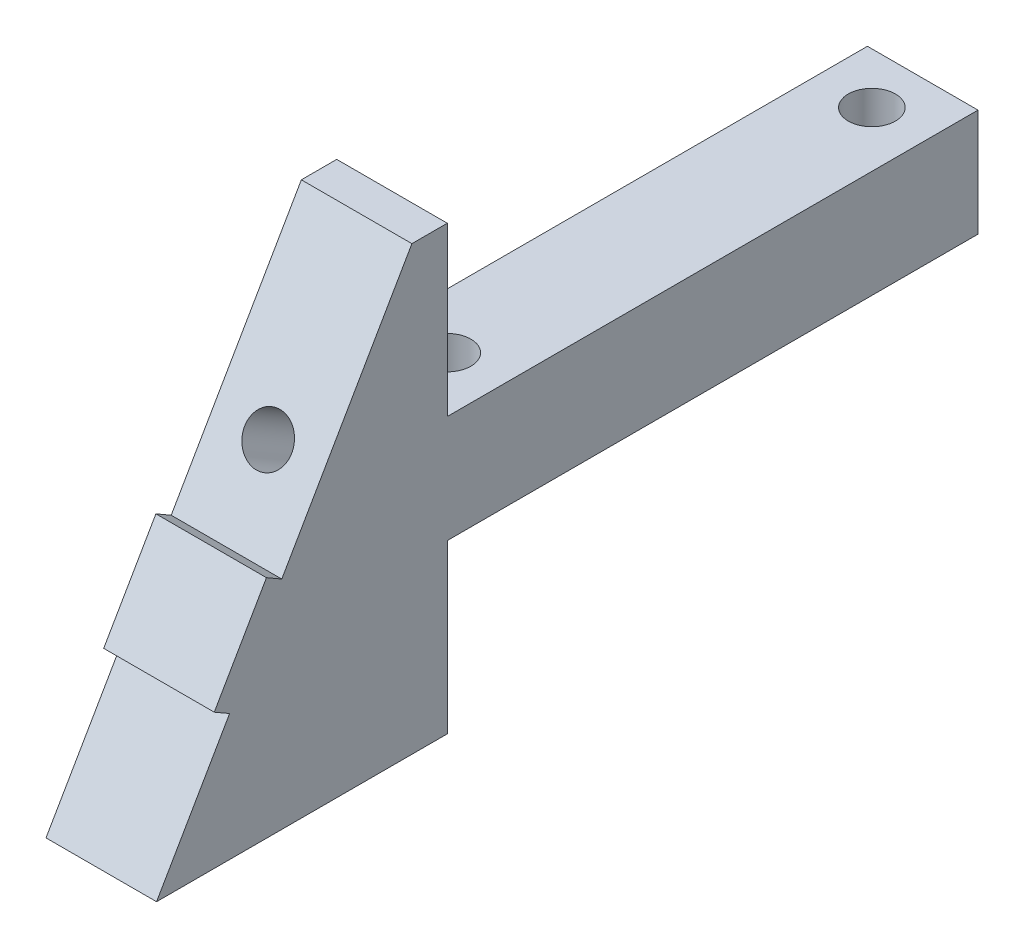
SolidWorks part; units mm, degrees
material "6061-T6 (SS)"
ref_plane "Front Plane" through (0, 0, 0) normal (0, 0, 1) x (1, 0, 0)
ref_plane "Top Plane" through (0, 0, 0) normal (0, 1, 0) x (1, 0, 0)
ref_plane "Right Plane" through (0, 0, 0) normal (1, 0, 0) x (0, 0, -1)
sketch "Sketch1" plane through (0, 0, 0) normal (1, 0, 0) x (0, 0, -1)
  line L0 (0, 0) -> (0, 25.4)
  line L1 (0, 25.4) -> (-2.032, 25.4)
  line L2 (-16.6967, 0) -> (0, 0)
  line L3 (-2.032, 25.4) -> (-16.6967, 0)
  dimension "D1" = 2.032
  dimension "D2" = 25.4
  dimension "D3" = 30
extrude "Boss-Extrude1" add sketch "Sketch1" along normal blind 6.35
sketch "Sketch2" plane through (0, 0, 0) normal (0, 0, -1) x (-1, 0, 0)
  line L0 (-6.35, 0) -> (-6.35, 25.4) construction
  line L1 (-6.35, 15.875) -> (0, 15.875)
  line L2 (-6.35, 15.875) -> (-6.35, 9.525)
  line L3 (-6.35, 9.525) -> (0, 9.525)
  line L4 (0, 15.875) -> (0, 9.525)
  line L5 (0, 0) -> (0, 25.4) construction
  line L7 (-6.35, 25.4) -> (0, 25.4) construction
  dimension "D1" = 6.35
  dimension "D2" = 9.525
extrude "Boss-Extrude2" add sketch "Sketch2" along normal blind 30.48
sketch "Sketch10" plane through (0, 7.2299, 12.5225) normal (0, 0.5, 0.866) x (1, 0, 0)
  line L0 (0, 20.981) -> (0, -8.3483) construction
  line L1 (0, 6.122) -> (6.35, 6.122)
  line L2 (0, 6.122) -> (0, -0.0502)
  line L3 (0, -0.0502) -> (6.35, -0.0502)
  line L4 (6.35, 6.122) -> (6.35, -0.0502)
  line L5 (6.35, 20.981) -> (6.35, -8.3483) construction
  line L6 (6.35, 20.981) -> (0, 20.981) construction
  dimension "D1" = 6.1722
  dimension "D2" = 14.859
extrude "Boss-Extrude3" add sketch "Sketch10" along normal blind 1.016
hole_wizard "Tap Drill for #6-32 Tap4" positions "Sketch12" profile "Sketch11" hole size "#6-32" standard "ANSI Inch"
sketch "Sketch12" plane through (0, 7.2299, 12.5225) normal (0, 0.5, 0.866) x (1, 0, 0)
  line L0 (6.35, 20.981) -> (0, 20.981) construction
  line L1 (0, 20.981) -> (0, 6.122) construction
  point P0 (3.175, 10.821)
  dimension "D1" = 10.16
  dimension "D2" = 3.175
sketch "Sketch11" plane through (3.175, 16.6012, 7.112) normal (1, 0, 0) x (0, -0.866, 0.5)
  line L0 (0, 0) -> (0, 7.1627)
  line L1 (0, 7.1627) -> (1.3525, 6.35)
  line L2 (1.3525, 6.35) -> (1.3525, 0)
  line L5 (1.3525, 0) -> (0, 0)
  line L10 (0, 7.1627) -> (-1.3525, 6.35) construction
  line L11 (0, -6.35) -> (0, 107.95) construction
  dimension "Hole Dia." = 2.7051
  dimension "Hole Depth" = 6.35
  dimension "Drill Angle" = 118
hole_wizard "Tap Drill for #6-32 Tap3" positions "Sketch9" profile "Sketch8" hole size "#6-32" standard "ANSI Inch" end condition through all
sketch "Sketch9" plane through (0, 15.875, 0) normal (0, 1, 0) x (1, 0, 0)
  line L0 (6.35, 30.48) -> (6.35, 0) construction
  line L1 (0, 0) -> (6.35, 0) construction
  point P0 (3.175, 3.175)
  point P2 (3.175, 27.559)
  dimension "D1" = 3.175
  dimension "D2" = 3.175
  dimension "D3" = 3.175
  dimension "D4" = 27.559
sketch "Sketch8" plane through (3.175, 15.875, -3.175) normal (1, 0, 0) x (0, 0, 1)
  line L0 (0, 0) -> (0, 15.875)
  line L1 (0, 15.875) -> (1.3525, 15.875)
  line L2 (1.3525, 15.875) -> (1.3525, 0)
  line L5 (1.3525, 0) -> (0, 0)
  line L11 (0, -6.35) -> (0, 107.95) construction
  dimension "Thru Hole Dia." = 2.7051
  dimension "Thru Hole Depth" = 15.875
sketch "Sketch13" plane through (0, 15.875, 0) normal (0, 1, 0) x (1, 0, 0)
  line L1 (0, 30.48) -> (6.35, 30.48)
  line L2 (0, 30.48) -> (0, 0)
  line L3 (0, 0) -> (6.35, 0)
  line L4 (6.35, 30.48) -> (6.35, 0)
extrude "Cut-Extrude1" cut sketch "Sketch13" against normal blind 0.0889
sketch "Sketch14" plane through (0, 9.525, 0) normal (0, -1, 0) x (1, 0, 0)
  line L1 (6.35, -30.48) -> (0, -30.48)
  line L2 (6.35, -30.48) -> (6.35, 0)
  line L3 (6.35, 0) -> (0, 0)
  line L4 (0, -30.48) -> (0, 0)
extrude "Cut-Extrude2" cut sketch "Sketch14" against normal blind 0.0889
sketch "Sketch15" plane through (0, 5.3018, -3.061) normal (0, 0.866, -0.5) x (1, 0, 0)
  line L1 (6.35, -14.4598) -> (0, -14.4598)
  line L2 (6.35, -14.4598) -> (6.35, -15.4758)
  line L3 (6.35, -15.4758) -> (0, -15.4758)
  line L4 (0, -14.4598) -> (0, -15.4758)
extrude "Cut-Extrude3" cut sketch "Sketch15" against normal blind 0.0889
sketch "Sketch16" plane through (0, -0.0434, 0.0251) normal (0, -0.866, 0.5) x (1, 0, 0)
  line L1 (0, 14.4598) -> (6.35, 14.4598)
  line L2 (0, 14.4598) -> (0, 15.4758)
  line L3 (0, 15.4758) -> (6.35, 15.4758)
  line L4 (6.35, 14.4598) -> (6.35, 15.4758)
extrude "Cut-Extrude4" cut sketch "Sketch16" against normal blind 0.0889
